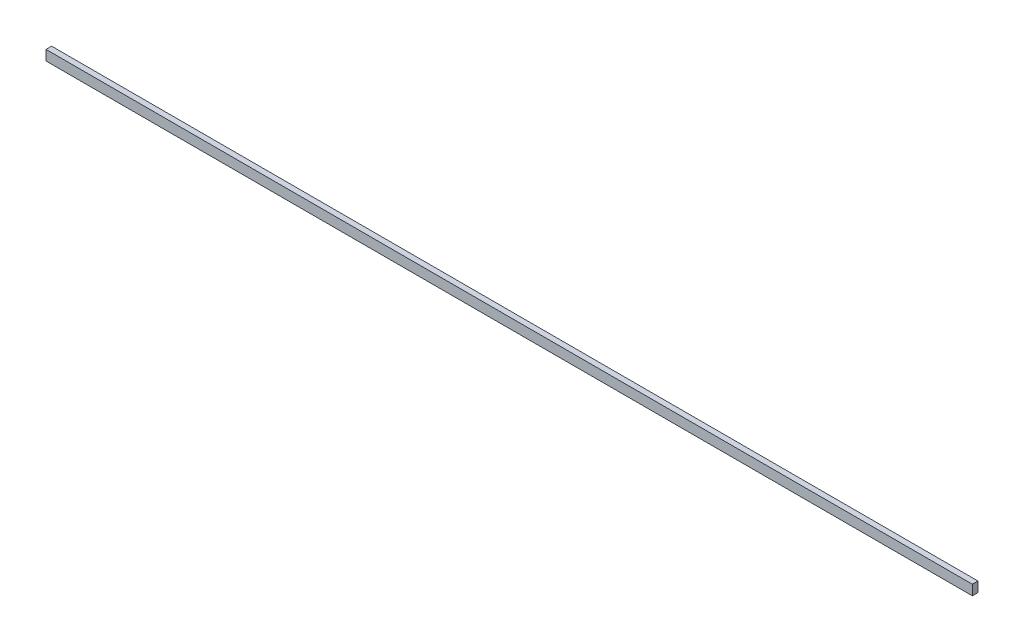
SolidWorks part; units mm, degrees
material "Фанера"
ref_plane "Front Plane" through (0, 0, 0) normal (0, 0, 1) x (1, 0, 0)
ref_plane "Top Plane" through (0, 0, 0) normal (0, 1, 0) x (1, 0, 0)
ref_plane "Right Plane" through (0, 0, 0) normal (1, 0, 0) x (0, 0, -1)
sketch "Эскиз2" plane through (0, 0, 0) normal (0, 0, 1) x (1, 0, 0)
  line L1 (-230.6, -2.5) -> (230.6, -2.5)
  line L2 (-230.6, -2.5) -> (-230.6, 2.5)
  line L3 (-230.6, 2.5) -> (230.6, 2.5)
  line L4 (230.6, -2.5) -> (230.6, 2.5)
  line L5 (-230.6, -2.5) -> (230.6, 2.5) construction
  line L6 (-230.6, 2.5) -> (230.6, -2.5) construction
  point P0 (0, 0)
  point P5 (230.6, 0)
  dimension "D1" = 5
  dimension "D2" = 461.2
extrude "Бобышка-Вытянуть1" add sketch "Эскиз2" along normal mid plane 2.8
